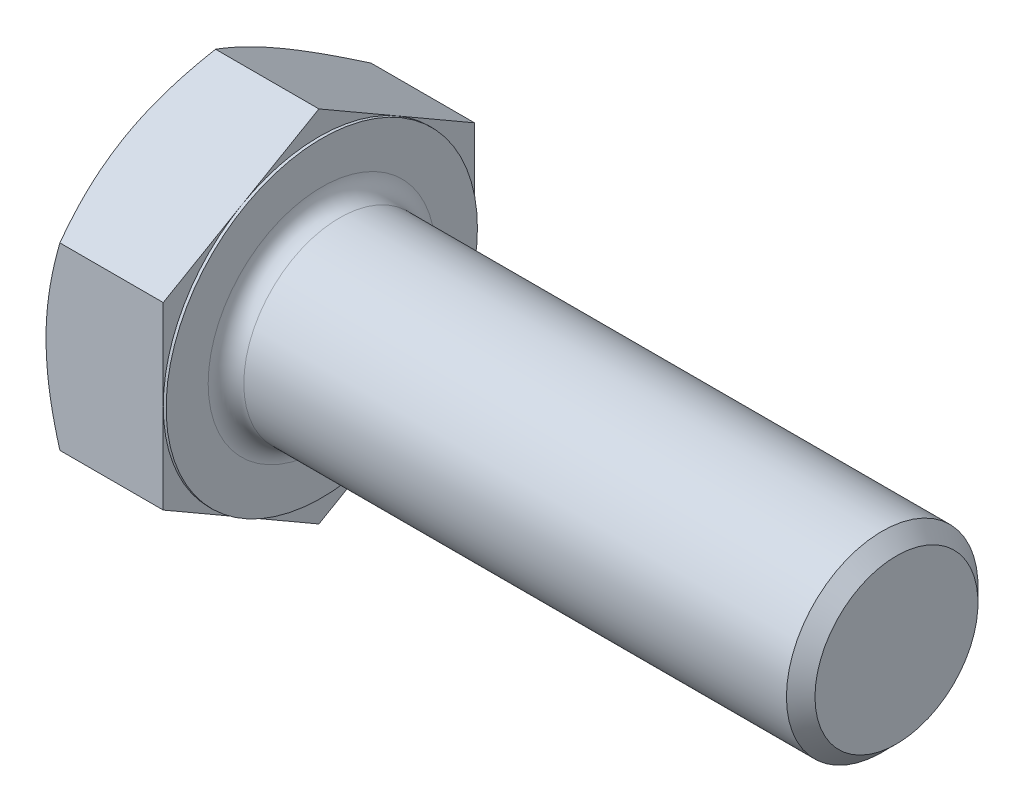
SolidWorks part; units mm, degrees
extrude "BaseHead" add sketch "Sketch1" along normal blind 15.9258
sketch "Sketch1" plane through (0, 0, 0) normal (1, 0, 0) x (0, 0, -1)
  line L0 (20.6375, 11.9151) -> (20.6375, -11.9151)
  line L1 (-20.6375, 11.9151) -> (-20.6375, -11.9151)
  line L2 (20.6375, -11.9151) -> (0, -23.8301)
  line L3 (0, -23.8301) -> (-20.6375, -11.9151)
  line L4 (20.6375, 11.9151) -> (0, 23.8301)
  line L5 (0, 23.8301) -> (-20.6375, 11.9151)
  dimension "Width_flats" = 41.275
  dimension "D2" = 120
  dimension "D3" = 20.6375
  dimension "D4" = 20.6375
  dimension "D5" = 20.6375
revolve "HeadChamfer" cut sketch "Sketch3" angle 360 about L6
sketch "Sketch3" plane through (0, 0, 0) normal (0, 0, 1) x (1, 0, 0)
  line L0 (0, 20.6375) -> (5.5094, 30.1801)
  line L1 (0, 23.8301) -> (0, 11.9151) construction
  line L2 (5.5094, 30.1801) -> (5.5094, 36.5301)
  line L3 (5.5094, 36.5301) -> (-12.7, 36.5301)
  line L4 (-12.7, 36.5301) -> (-12.7, 20.6375)
  line L5 (-12.7, 20.6375) -> (0, 20.6375)
  line L6 (0, 0) -> (99.06, 0) construction
  line L7 (15.9258, 23.8301) -> (0, 23.8301) construction
  dimension "D1" = 20.6375
  dimension "D2" = 6.35
  dimension "D3" = 12.7
  dimension "D4" = 6.35
  dimension "Head_ch_ang" = 30
ref_plane "Plane1" through (0, 0, 0) normal (0, 0, 1) x (1, 0, 0)
ref_plane "Plane2" through (0, 0, 0) normal (0, 1, 0) x (1, 0, 0)
ref_plane "Plane3" through (0, 0, 0) normal (1, 0, 0) x (0, 0, -1)
sketch "BodySke" plane through (0, 0, 0) normal (0, 0, 1) x (1, 0, 0)
  line L0 (0, 11.9151) -> (0, -11.9151) construction
  line L1 (0, 0) -> (92.1258, 0)
  line L2 (0, 0) -> (0, 12.7)
  line L3 (0, 12.7) -> (90.2335, 12.7)
  line L4 (92.1258, 0) -> (92.1258, 10.8077)
  line L5 (15.9258, 23.8301) -> (15.9258, 11.9151) construction
  line L6 (92.1258, 10.8077) -> (90.2335, 12.7)
  line L7 (0, 0) -> (96.52, 0) construction
  line L8 (92.1258, -10.8077) -> (90.2335, -12.7) construction
  line L9 (0, -12.7) -> (90.2335, -12.7) construction
  line L10 (18.034, 15.24) -> (18.034, -1.27) construction
  line L11 (60.3758, 15.24) -> (60.3758, -1.27) construction
  line L12 (15.9258, 11.9151) -> (15.9258, -11.9151) construction
  dimension "Diameter" = 25.4
revolve "BaseBody" add sketch "BodySke" angle 360 about L7
cosmetic thread "ThreadCosmetic" [suppressed] parameters "Thread_length"=31.75, "Thread_minor"=21.6154
sketch "Sketch4" plane through (0, 0, 0) normal (0, 0, 1) x (1, 0, 0)
  line L1 (15.9258, 23.8301) -> (15.9258, 11.9151) construction
  line L2 (15.9258, 20.6375) -> (15.5448, 20.6375)
  line L3 (15.9258, 20.6375) -> (15.9258, 49.2301)
  line L4 (15.9258, 49.2301) -> (15.5448, 49.2301)
  line L5 (0, 0) -> (95.25, 0) construction
  line L6 (0, 0) -> (96.52, 0) construction
  line L7 (15.5448, 20.6375) -> (15.5448, 49.2301)
  line L8 (15.9258, 23.8301) -> (1.8433, 23.8301) construction
  dimension "D1" = 20.6375
  dimension "D2" = 25.4
revolve "BearingFace" cut sketch "Sketch4" angle 360 about L5
fillet "HeadFillet" radius 2.3622 1 edges at (15.9258, 0, -12.7)
sketch "ThdSchSke" plane through (0, 0, 0) normal (0, 0, 1) x (1, 0, 0)
  line L0 (60.3758, -10.8077) -> (59.0508, -12.7)
  line L1 (60.3758, -10.8077) -> (61.7008, -12.7)
  line L2 (61.7008, -12.7) -> (61.7008, -15.875)
  line L3 (-3.175, 0) -> (5.1513, 0) construction
  line L5 (61.7008, -15.875) -> (59.0508, -15.875)
  line L6 (59.0508, -15.875) -> (59.0508, -12.7)
  dimension "Thread_minor" = 21.6154
  dimension "Diameter" = 25.4
  dimension "Start" = 60.3758
revolve "ThreadSchematic" [suppressed] cut sketch "ThdSchSke" angle 360 about L3
pattern_linear "ThdSchPat" [suppressed]
equation "\"D3@Sketch1\" = \"Width_flats@Sketch1\" / 2"
equation "\"D4@Sketch1\" = \"D3@Sketch1\""
equation "\"D5@Sketch1\" = \"D4@Sketch1\""
equation "\"Thread_minor@ThreadCosmetic\" = \"Minor_dia@BodySke\""
equation "\"D1@Sketch3\" = \"Width_flats@Sketch1\" / 2"
equation "\"D1@Sketch4\" = \"Width_flats@Sketch1\" / 2"
equation "\"Thread_length@ThreadCosmetic\" = ((sgn( (\"Length@BodySke\" - \"Advance@BodySke\" ) - \"Thread_nom@BodySke\" )-1)*( (\"Length@BodySke\" - \"Advance@BodySke\" ) - \"Thread_nom@BodySke\" ))/-2+ \"Thread_nom@BodySke\""
equation "\"Thread_minor@ThdSchSke\" = \"Minor_dia@BodySke\""
equation "\"Diameter@ThdSchSke\" = \"Diameter@BodySke\""
equation "\"Overcut@ThdSchSke\" = \"Diameter@BodySke\" * 1.25"
equation "\"Start@ThdSchSke\" = \"Head_ht@BaseHead\" + \"Length@BodySke\" - \"Thread_length@ThreadCosmetic\"  '---Non-countersunk---"
equation "\"Num_threads@ThdSchPat\" = int( \"Thread_length@ThreadCosmetic\" / \"Advance@BodySke\" + 0.999 )  + 1"
equation "\"Advance@ThdSchPat\" = \"Thread_length@ThreadCosmetic\" /  (\"Num_threads@ThdSchPat\" - 1) 'relax it"
equation "\"Num_threads@ThdSchPat\" = \"Num_threads@ThdSchPat\" - sgn( \"Num_threads@ThdSchPat\" - 1) '---chamfered tips only---"
